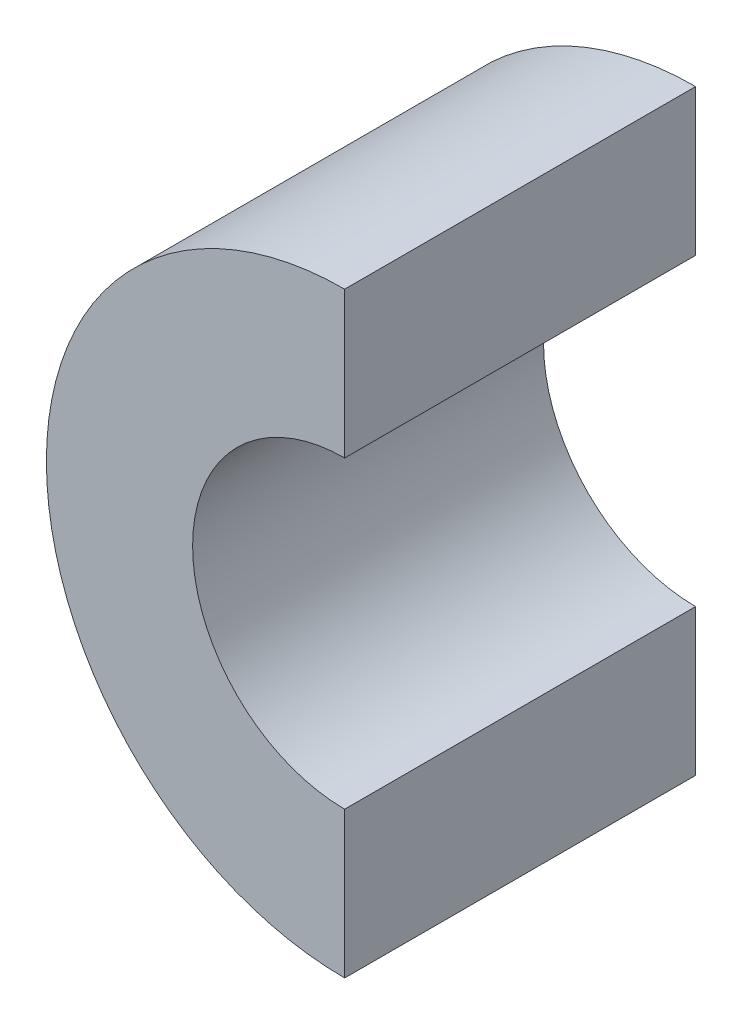
SolidWorks part; units mm, degrees
ref_plane "Front Plane" through (0, 0, 0) normal (0, 0, 1) x (1, 0, 0)
ref_plane "Top Plane" through (0, 0, 0) normal (0, 1, 0) x (1, 0, 0)
ref_plane "Right Plane" through (0, 0, 0) normal (1, 0, 0) x (0, 0, -1)
sketch "Sketch1" plane through (0, 0, 0) normal (0, 0, 1) x (1, 0, 0)
  line L0 (0, 10.2) -> (0, 5.2)
  line L1 (0, -5.2) -> (0, -10.2)
  arc A0 (0, 5.2) -> (0, -5.2) centre (0, 0) ccw
  arc A1 (0, 10.2) -> (0, -10.2) centre (0, 0) ccw
  dimension "D1" = 5.2
  dimension "D2" = 5
extrude "Boss-Extrude1" add sketch "Sketch1" along normal blind 12
